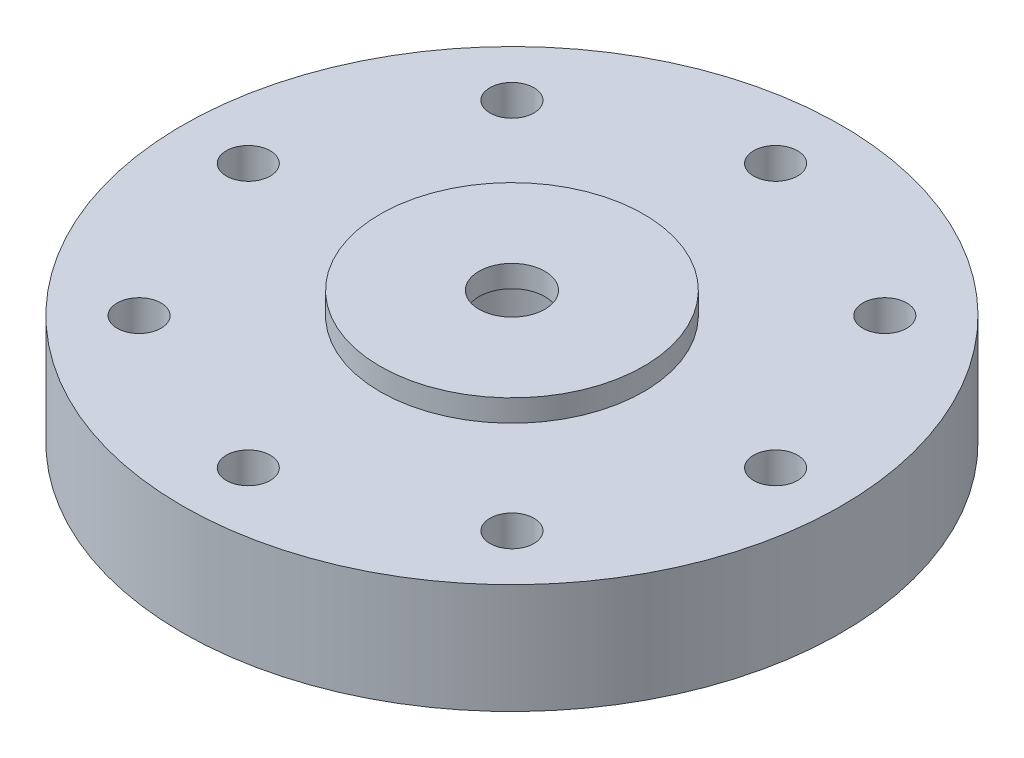
SolidWorks part; units mm, degrees
ref_plane "Front Plane" through (0, 0, 0) normal (0, 0, 1) x (1, 0, 0)
ref_plane "Top Plane" through (0, 0, 0) normal (0, 1, 0) x (1, 0, 0)
ref_plane "Right Plane" through (0, 0, 0) normal (1, 0, 0) x (0, 0, -1)
sketch "Sketch1" plane through (0, 0, 0) normal (0, 1, 0) x (1, 0, 0)
  line L0 (0, 15) -> (0, -15) construction
  line L1 (-15, 0) -> (15, 0) construction
  circle A0 centre (0, 0) radius 15
  circle A1 centre (0, 12) radius 1
  circle A2 centre (8.4853, 8.4853) radius 1
  circle A3 centre (12, 0) radius 1
  circle A4 centre (8.4853, -8.4853) radius 1
  circle A5 centre (0, -12) radius 1
  circle A6 centre (-8.4853, -8.4853) radius 1
  circle A7 centre (-12, 0) radius 1
  circle A8 centre (-8.4853, 8.4853) radius 1
  point P25 (0, 0)
  dimension "D1" = 3
  dimension "D2" = 8
extrude "Boss-Extrude1" add sketch "Sketch1" along normal blind 5
sketch "Sketch2" plane through (0, 5, 0) normal (0, 1, 0) x (1, 0, 0)
  circle A0 centre (0, 0) radius 6
extrude "Boss-Extrude2" add sketch "Sketch2" along normal blind 1
sketch "Sketch3" plane through (0, 0, 0) normal (0, -1, 0) x (1, 0, 0)
  circle A0 centre (0, 0) radius 3
extrude "Cut-Extrude1" cut sketch "Sketch3" against normal blind 5
sketch "Sketch4" plane through (0, 6, 0) normal (0, 1, 0) x (1, 0, 0)
  circle A0 centre (0, 0) radius 1.5
extrude "Cut-Extrude2" cut sketch "Sketch4" against normal blind 5
